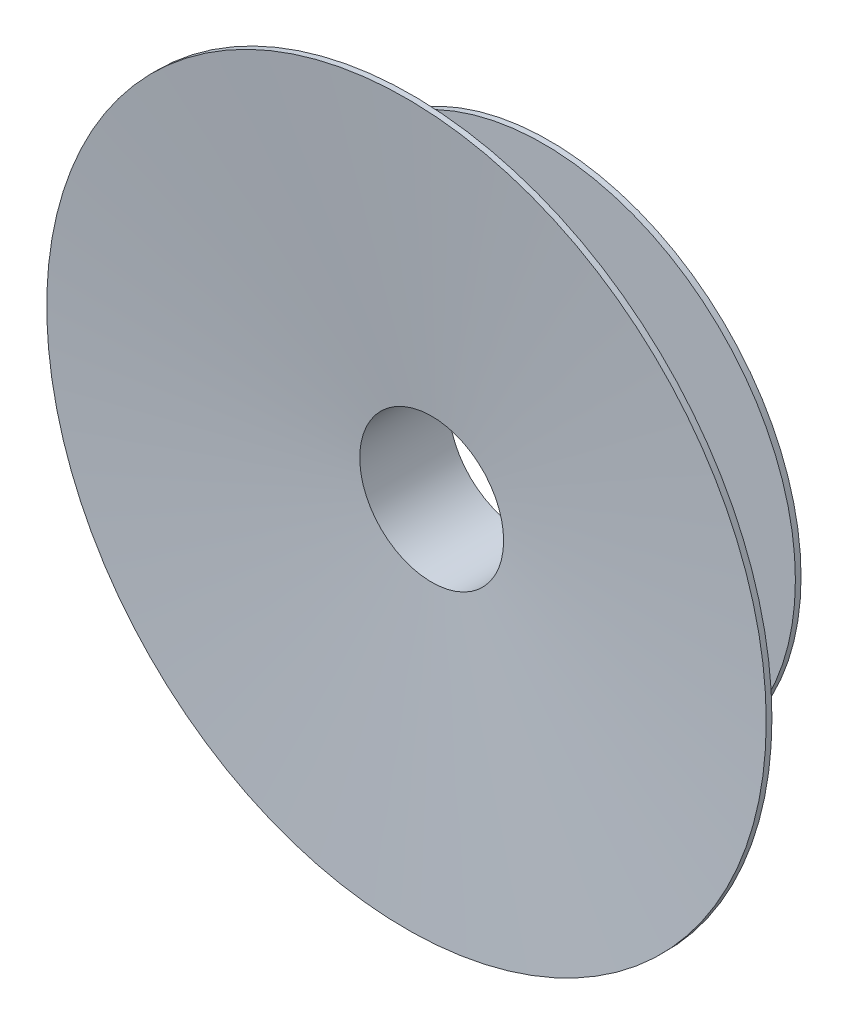
SolidWorks part; units mm, degrees
material "6061-T6 (SS)"
ref_plane "Front Plane" through (0, 0, 0) normal (1, 0, 0) x (0, 1, 0)
ref_plane "Top Plane" through (0, 0, 0) normal (0, 0, 1) x (0, 1, 0)
ref_plane "Right Plane" through (0, 0, 0) normal (0, 1, 0) x (-1, 0, 0)
ref_axis "Axis1" through (0, 0, 14.052) along (0, 0, -1)
sketch "Sketch1" plane through (0, 0, 0) normal (1, 0, 0) x (0, 1, 0)
  line L0 (0, 0) -> (-25.4, 0) construction
  line L1 (-25.4, -24.5) -> (-25.4, 2)
  line L2 (-25.4, 2) -> (-127, 10.8888)
  line L3 (-127, 10.8888) -> (-127, 8.8812)
  line L9 (-127, 8.8812) -> (-27.4, 0.1673)
  line L10 (-27.4, 0.1673) -> (-27.4, -23.6837)
  line L12 (-57.15, -37.5) -> (-88.9, -37.5)
  line L16 (-88.9, -39.5) -> (-57.15, -39.5)
  line L21 (-57.15, -39.5) -> (-57.15, -49.5) construction
  line L22 (0, 0) -> (0, -49.5) construction
  line L23 (-57.15, -49.5) -> (0, -49.5) construction
  line L24 (-57.15, -39.5) -> (-57.15, -37.5) construction
  line L25 (-25.4, -24.5) -> (-25.4, -29.5)
  line L26 (-25.4, -29.5) -> (-31.1064, -29.5)
  line L27 (-88.9, -37.5) -> (-88.9, -39.5)
  arc A0 (-57.15, -39.5) -> (-25.4, -24.5) centre (-61.6379, 11.1014) ccw
  arc A1 (-57.15, -37.5) -> (-27.4, -23.6837) centre (-61.6379, 11.1014) ccw
  dimension "D1" = 2
  dimension "D10" = 50.8
  dimension "D2" = 2
  dimension "D3" = 25.4
  dimension "D4" = 127
  dimension "D5" = 85
  dimension "D6" = 2
  dimension "D7" = 24.5
  dimension "D8" = 57.15
  dimension "D9" = 88.9
  dimension "D11" = 10
  dimension "D13" = 2
  dimension "D14" = 39.5
  dimension "D16" = 29.5
revolve "Revolve1" add sketch "Sketch1" angle 360 about axis through (0, 0, 14.052) along (0, 0, -1)
